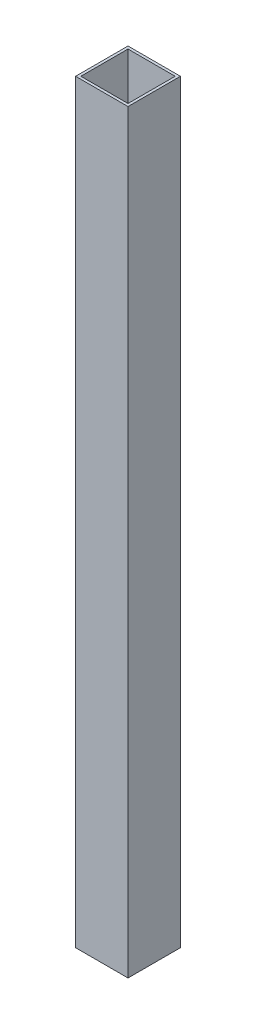
SolidWorks part; units mm, degrees
ref_plane "Front Plane" through (0, 0, 0) normal (0, 0, 1) x (1, 0, 0)
ref_plane "Top Plane" through (0, 0, 0) normal (0, 1, 0) x (1, 0, 0)
ref_plane "Right Plane" through (0, 0, 0) normal (1, 0, 0) x (0, 0, -1)
sketch "Sketch1" plane through (0, 0, 0) normal (0, 1, 0) x (1, 0, 0)
  line L1 (-12.5, 12.5) -> (12.5, 12.5)
  line L2 (-12.5, 12.5) -> (-12.5, -12.5)
  line L3 (-12.5, -12.5) -> (12.5, -12.5)
  line L4 (12.5, 12.5) -> (12.5, -12.5)
  line L5 (-12.5, 12.5) -> (12.5, -12.5) construction
  line L6 (-12.5, -12.5) -> (12.5, 12.5) construction
  line L7 (11.2504, 11.2504) -> (-11.2504, 11.2504)
  line L8 (11.2504, 11.2504) -> (11.2504, -11.2504)
  line L9 (11.2504, -11.2504) -> (-11.2504, -11.2504)
  line L10 (-11.2504, 11.2504) -> (-11.2504, -11.2504)
  line L11 (11.2504, 11.2504) -> (-11.2504, -11.2504) construction
  line L12 (11.2504, -11.2504) -> (-11.2504, 11.2504) construction
  point P0 (0, 0)
  point P6 (0, 0)
extrude "Boss-Extrude1" add sketch "Sketch1" along normal blind 360
